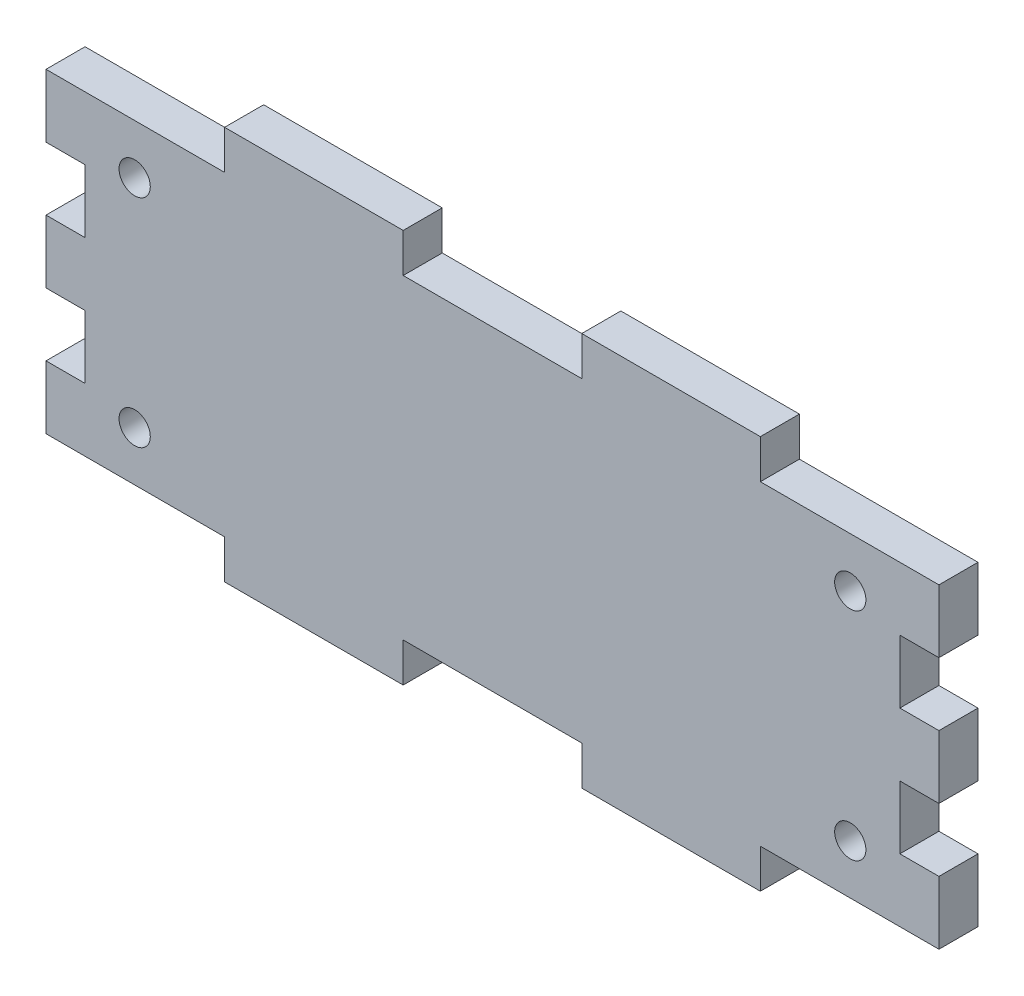
SolidWorks part; units mm, degrees
ref_plane "Front Plane" through (0, 0, 0) normal (0, 0, 1) x (1, 0, 0)
ref_plane "Top Plane" through (0, 0, 0) normal (0, 1, 0) x (1, 0, 0)
ref_plane "Right Plane" through (0, 0, 0) normal (1, 0, 0) x (0, 0, -1)
ref_plane "Plane1" through (183.8691, 52.5344, 10) normal (-1, 0, 0) x (0, 0, 1)
sketch "Sketch3" plane through (0, 0, 0) normal (0, 0, 1) x (1, 0, 0)
  line L4 (148.1491, 78.2878) -> (102.4291, 78.2878)
  line L12 (183.8691, 68.2878) -> (148.1491, 68.2878)
  line L18 (-34.7309, 78.2878) -> (-34.7309, -22.5122) construction
  line L24 (102.4291, 78.2878) -> (102.4291, 68.2878)
  line L25 (148.1491, 78.2878) -> (148.1491, 68.2878)
  line L26 (-34.7309, 35.9678) -> (-34.7309, 19.8078)
  line L27 (79.5691, 68.2878) -> (79.5691, 55.5878) construction
  line L29 (183.8691, 68.2878) -> (-24.7309, 68.2878) construction
  line L30 (102.4291, 68.2878) -> (56.7091, 68.2878)
  line L31 (193.8691, 78.2878) -> (-34.7309, 78.2878) construction
  line L33 (-34.7309, 68.2878) -> (-34.7309, 52.1278)
  line L34 (183.8691, 68.2878) -> (193.8691, 68.2878)
  line L35 (193.8691, 78.2878) -> (193.8691, -22.5122) construction
  line L36 (-24.7309, 68.2878) -> (-24.7309, -12.5122) construction
  line L37 (183.8691, -12.5122) -> (-24.7309, -12.5122) construction
  line L38 (193.8691, -22.5122) -> (-34.7309, -22.5122) construction
  line L39 (183.8691, 68.2878) -> (183.8691, -12.5122) construction
  line L40 (183.8691, 52.1278) -> (183.8691, 35.9678)
  line L41 (183.8691, 52.1278) -> (193.8691, 52.1278)
  line L42 (183.8691, 35.9678) -> (193.8691, 35.9678)
  line L43 (183.8691, 27.8878) -> (193.8691, 27.8878) construction
  line L44 (193.8691, 68.2878) -> (193.8691, 52.1278)
  line L45 (183.8691, 19.8078) -> (193.8691, 19.8078) [skipped]
  line L46 (183.8691, 3.6478) -> (193.8691, 3.6478) [skipped]
  line L47 (193.8691, 35.9678) -> (193.8691, 19.8078)
  line L48 (-24.7309, 27.8878) -> (-34.7309, 27.8878) construction
  line L49 (-24.7309, 35.9678) -> (-34.7309, 35.9678)
  line L50 (-24.7309, 52.1278) -> (-34.7309, 52.1278)
  line L51 (-24.7309, 52.1278) -> (-24.7309, 35.9678)
  line L52 (-24.7309, 68.2878) -> (-34.7309, 68.2878)
  line L53 (10.9891, 78.2878) -> (10.9891, 68.2878)
  line L54 (56.7091, 78.2878) -> (56.7091, 68.2878)
  line L55 (-24.7309, 68.2878) -> (10.9891, 68.2878)
  line L56 (10.9891, 78.2878) -> (56.7091, 78.2878)
  line L57 (148.1491, 78.2878) -> (102.4291, 78.2878)
  line L58 (183.8691, 68.2878) -> (148.1491, 68.2878)
  line L59 (102.4291, 78.2878) -> (102.4291, 68.2878)
  line L60 (148.1491, 78.2878) -> (148.1491, 68.2878)
  line L61 (183.8691, 68.2878) -> (193.8691, 68.2878)
  line L62 (183.8691, 52.1278) -> (183.8691, 35.9678)
  line L63 (183.8691, 52.1278) -> (193.8691, 52.1278)
  line L64 (183.8691, 35.9678) -> (193.8691, 35.9678)
  line L65 (183.8691, 27.8878) -> (193.8691, 27.8878) construction
  line L66 (-34.7309, 35.9678) -> (-34.7309, 19.8078)
  line L67 (-34.7309, 68.2878) -> (-34.7309, 52.1278)
  line L68 (-24.7309, 27.8878) -> (-34.7309, 27.8878) construction
  line L69 (-24.7309, 35.9678) -> (-34.7309, 35.9678)
  line L70 (-24.7309, 52.1278) -> (-34.7309, 52.1278)
  line L71 (-24.7309, 52.1278) -> (-24.7309, 35.9678)
  line L72 (-24.7309, 68.2878) -> (-34.7309, 68.2878)
  line L73 (193.8691, 68.2878) -> (193.8691, 52.1278)
  line L74 (193.8691, 35.9678) -> (193.8691, 19.8078)
  line L75 (10.9891, 78.2878) -> (10.9891, 68.2878)
  line L76 (56.7091, 78.2878) -> (56.7091, 68.2878)
  line L77 (-24.7309, 68.2878) -> (10.9891, 68.2878)
  line L78 (10.9891, 78.2878) -> (56.7091, 78.2878)
  line L79 (79.5691, -12.5122) -> (79.5691, 0.1878) construction
  line L80 (10.9891, -22.5122) -> (56.7091, -22.5122)
  line L81 (-24.7309, -12.5122) -> (10.9891, -12.5122)
  line L82 (56.7091, -22.5122) -> (56.7091, -12.5122)
  line L83 (10.9891, -22.5122) -> (10.9891, -12.5122)
  line L84 (193.8691, -12.5122) -> (193.8691, 3.6478)
  line L85 (-24.7309, -12.5122) -> (-34.7309, -12.5122)
  line L86 (-24.7309, 3.6478) -> (-24.7309, 19.8078)
  line L87 (-24.7309, 3.6478) -> (-34.7309, 3.6478)
  line L88 (-24.7309, 19.8078) -> (-34.7309, 19.8078)
  line L89 (-34.7309, -12.5122) -> (-34.7309, 3.6478)
  line L90 (183.8691, 19.8078) -> (193.8691, 19.8078)
  line L91 (183.8691, 3.6478) -> (193.8691, 3.6478)
  line L92 (183.8691, 3.6478) -> (183.8691, 19.8078)
  line L93 (183.8691, -12.5122) -> (193.8691, -12.5122)
  line L94 (148.1491, -22.5122) -> (148.1491, -12.5122)
  line L95 (102.4291, -22.5122) -> (102.4291, -12.5122)
  line L96 (183.8691, -12.5122) -> (148.1491, -12.5122)
  line L97 (148.1491, -22.5122) -> (102.4291, -22.5122)
  line L98 (10.9891, -22.5122) -> (56.7091, -22.5122)
  line L99 (-24.7309, -12.5122) -> (10.9891, -12.5122)
  line L100 (56.7091, -22.5122) -> (56.7091, -12.5122)
  line L101 (10.9891, -22.5122) -> (10.9891, -12.5122)
  line L102 (-24.7309, -12.5122) -> (-34.7309, -12.5122)
  line L103 (-24.7309, 3.6478) -> (-24.7309, 19.8078)
  line L104 (-24.7309, 3.6478) -> (-34.7309, 3.6478)
  line L105 (-24.7309, 19.8078) -> (-34.7309, 19.8078)
  line L106 (193.8691, -12.5122) -> (193.8691, 3.6478)
  line L107 (183.8691, 19.8078) -> (193.8691, 19.8078)
  line L108 (183.8691, 3.6478) -> (193.8691, 3.6478)
  line L109 (183.8691, 3.6478) -> (183.8691, 19.8078)
  line L110 (183.8691, -12.5122) -> (193.8691, -12.5122)
  line L111 (-34.7309, -12.5122) -> (-34.7309, 3.6478)
  line L112 (102.4291, -12.5122) -> (56.7091, -12.5122)
  line L113 (148.1491, -22.5122) -> (148.1491, -12.5122)
  line L114 (102.4291, -22.5122) -> (102.4291, -12.5122)
  line L115 (183.8691, -12.5122) -> (148.1491, -12.5122)
  line L116 (148.1491, -22.5122) -> (102.4291, -22.5122)
  circle A1 centre (171.1691, 55.5878) radius 4
  circle A5 centre (-12.0309, 55.5878) radius 4
  circle A6 centre (171.1691, 55.5878) radius 4
  circle A7 centre (-12.0309, 55.5878) radius 4
  circle A8 centre (-12.0309, 0.1878) radius 4
  circle A9 centre (171.1691, 0.1878) radius 4
  circle A10 centre (-12.0309, 0.1878) radius 4
  circle A11 centre (171.1691, 0.1878) radius 4
  point P10 (79.5691, 27.8878)
  dimension "D1" = 5
  dimension "D5" = 10
extrude "Boss-Extrude2" add sketch "Sketch3" along normal blind 10 contours L112 L95 L97 L94 L96 L93 L84 L91 L92 L90 L47 L42 L40 L41 L44 L34 L12 L25 L4 L24 L30 L54 L56 L53 L55 L52 L33 L50 L51 L49 L26 L88 L86 L87 L89 L85 L81 L83 L80 L82 A5 A1 A8 A9
